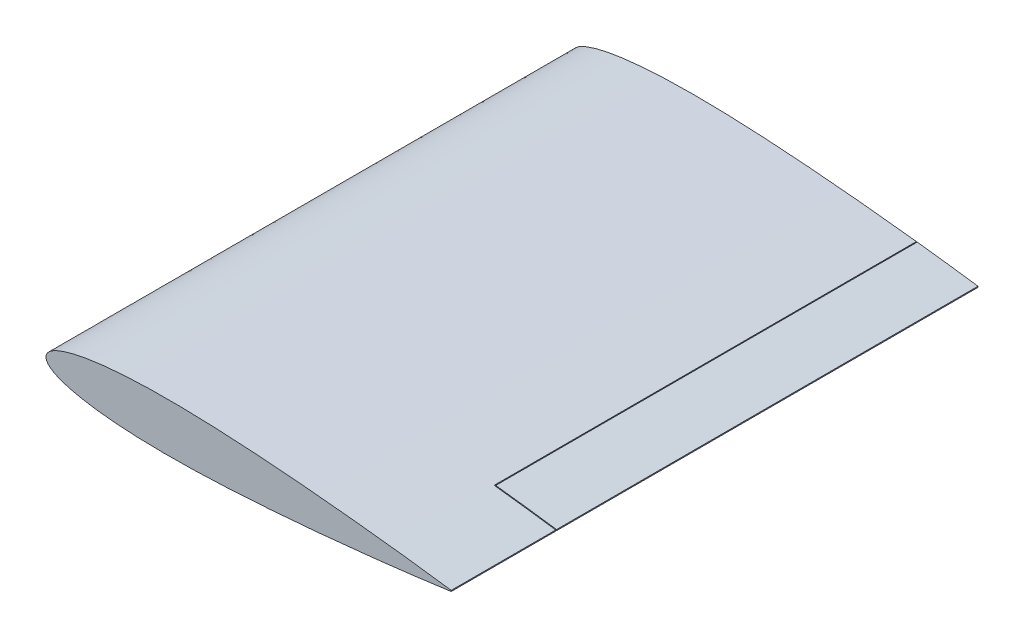
SolidWorks part; units mm, degrees
ref_plane "Front Plane" through (0, 0, 0) normal (0, 0, 1) x (1, 0, 0)
ref_plane "Top Plane" through (0, 0, 0) normal (0, 1, 0) x (1, 0, 0)
ref_plane "Right Plane" through (0, 0, 0) normal (1, 0, 0) x (0, 0, -1)
curve "Curve1"
  spline degree 3 poles (0, 0, 0) (0.003, 0.0365, 0) (0.009, 0.1114, 0) (0.0578, 0.22, 0) (0.134, 0.3245, 0) (0.2397, 0.4254, 0) (0.3736, 0.523, 0) (0.536, 0.6174, 0) (0.7264, 0.7086, 0) (0.9445, 0.7962, 0) (1.1898, 0.8801, 0) (1.462, 0.96, 0) (1.7603, 1.0355, 0) (2.0841, 1.1065, 0) (2.4327, 1.1725, 0) (2.8052, 1.2334, 0) (3.2008, 1.2888, 0) (3.6185, 1.3388, 0) (4.0575, 1.3829, 0) (4.5166, 1.4212, 0) (4.9948, 1.4535, 0) (5.491, 1.4798, 0) (6.0041, 1.5001, 0) (6.5327, 1.5144, 0) (7.0758, 1.5227, 0) (7.632, 1.5254, 0) (8.2001, 1.5224, 0) (8.7786, 1.514, 0) (9.3663, 1.5004, 0) (9.9618, 1.4819, 0) (10.5636, 1.4587, 0) (11.1705, 1.4311, 0) (11.7809, 1.3995, 0) (12.3935, 1.3642, 0) (13.0067, 1.3254, 0) (13.6193, 1.2836, 0) (14.2297, 1.2391, 0) (14.8366, 1.1921, 0) (15.4384, 1.1431, 0) (16.0339, 1.0922, 0) (16.6216, 1.0399, 0) (17.2001, 0.9864, 0) (17.7681, 0.9321, 0) (18.3242, 0.8771, 0) (18.8673, 0.8219, 0) (19.3959, 0.7666, 0) (19.9089, 0.7116, 0) (20.405, 0.657, 0) (20.8832, 0.6033, 0) (21.3422, 0.5505, 0) (21.7811, 0.499, 0) (22.1987, 0.449, 0) (22.5942, 0.4008, 0) (22.9666, 0.3545, 0) (23.3149, 0.3106, 0) (23.6385, 0.2691, 0) (23.9366, 0.2304, 0) (24.2084, 0.1946, 0) (24.4533, 0.1619, 0) (24.6708, 0.1326, 0) (24.8603, 0.1068, 0) (25.0214, 0.0847, 0) (25.1537, 0.0664, 0) (25.257, 0.052, 0) (25.3309, 0.0417, 0) (25.3753, 0.0355, 0) (25.3951, 0.0327, 0) (25.4, 0.032, 0) knots 0 0 0 0 0.004218 0.008652 0.013562 0.019137 0.0255 0.032726 0.040862 0.04993 0.05994 0.070892 0.082777 0.095581 0.109286 0.123868 0.139301 0.155557 0.172602 0.190404 0.208924 0.228125 0.247965 0.268401 0.289388 0.310881 0.332832 0.35519 0.377906 0.400928 0.424203 0.447679 0.471299 0.49501 0.518757 0.542484 0.566136 0.589657 0.612992 0.636087 0.658886 0.681338 0.703388 0.724985 0.746079 0.766619 0.786556 0.805845 0.82444 0.842296 0.859372 0.875627 0.891023 0.905523 0.919093 0.9317 0.943314 0.953909 0.963457 0.971937 0.979328 0.985613 0.990775 0.994804 0.997688 0.999422 1 1 1 1
curve "Curve2"
  spline degree 3 poles (0.0148, -0.1082, 0) (0.028, -0.1443, 0) (0.0559, -0.2205, 0) (0.1346, -0.3244, 0) (0.2395, -0.4254, 0) (0.3737, -0.523, 0) (0.536, -0.6174, 0) (0.7264, -0.7086, 0) (0.9445, -0.7962, 0) (1.1898, -0.8801, 0) (1.462, -0.96, 0) (1.7603, -1.0355, 0) (2.0841, -1.1065, 0) (2.4327, -1.1725, 0) (2.8052, -1.2334, 0) (3.2008, -1.2888, 0) (3.6185, -1.3388, 0) (4.0575, -1.3829, 0) (4.5166, -1.4212, 0) (4.9948, -1.4535, 0) (5.491, -1.4798, 0) (6.0041, -1.5001, 0) (6.5327, -1.5144, 0) (7.0758, -1.5227, 0) (7.632, -1.5254, 0) (8.2001, -1.5224, 0) (8.7786, -1.514, 0) (9.3663, -1.5004, 0) (9.9618, -1.4819, 0) (10.5636, -1.4587, 0) (11.1705, -1.4311, 0) (11.7809, -1.3995, 0) (12.3935, -1.3642, 0) (13.0067, -1.3254, 0) (13.6193, -1.2836, 0) (14.2297, -1.2391, 0) (14.8366, -1.1921, 0) (15.4384, -1.1431, 0) (16.0339, -1.0922, 0) (16.6216, -1.0399, 0) (17.2001, -0.9864, 0) (17.7681, -0.9321, 0) (18.3242, -0.8771, 0) (18.8673, -0.8219, 0) (19.3959, -0.7666, 0) (19.9089, -0.7116, 0) (20.405, -0.657, 0) (20.8832, -0.6033, 0) (21.3422, -0.5505, 0) (21.7811, -0.499, 0) (22.1987, -0.449, 0) (22.5942, -0.4008, 0) (22.9666, -0.3545, 0) (23.3149, -0.3106, 0) (23.6385, -0.2691, 0) (23.9366, -0.2304, 0) (24.2084, -0.1946, 0) (24.4533, -0.1619, 0) (24.6708, -0.1326, 0) (24.8603, -0.1068, 0) (25.0214, -0.0847, 0) (25.1537, -0.0664, 0) (25.257, -0.052, 0) (25.3309, -0.0417, 0) (25.3753, -0.0355, 0) (25.3951, -0.0327, 0) (25.4, -0.032, 0) knots 0 0 0 0 0.004453 0.009384 0.014983 0.021372 0.028629 0.036799 0.045906 0.055959 0.066957 0.078892 0.091751 0.105513 0.120157 0.135656 0.15198 0.169098 0.186975 0.205574 0.224856 0.24478 0.265302 0.286379 0.307962 0.330006 0.352459 0.375271 0.398391 0.421765 0.445339 0.46906 0.492871 0.516719 0.540546 0.564298 0.587919 0.611353 0.634545 0.657442 0.679988 0.702132 0.723821 0.745003 0.76563 0.785652 0.805023 0.823696 0.841628 0.858776 0.8751 0.890561 0.905123 0.91875 0.93141 0.943074 0.953713 0.963302 0.971818 0.979241 0.985552 0.990736 0.994782 0.997678 0.999419 1 1 1 1
sketch "Sketch1" plane through (0, 0, 0) normal (0, 0, 1) x (1, 0, 0)
  line L0 (0, 0) -> (0.0742, -0.5411)
  line L1 (127, 0.16) -> (127, -0.16)
  spline S2 degree 3 poles (0.0742, -0.5411) (0.1402, -0.7217) (0.2794, -1.1023) (0.673, -1.6219) (1.1974, -2.1272) (1.8685, -2.615) (2.6798, -3.0872) (3.6318, -3.5429) (4.7223, -3.9812) (5.9492, -4.4007) (7.31, -4.8) (8.8016, -5.1777) (10.4206, -5.5323) (12.1634, -5.8624) (14.0259, -6.1668) (16.0039, -6.4442) (18.0926, -6.6938) (20.2874, -6.9146) (22.583, -7.106) (24.9741, -7.2675) (27.4552, -7.3989) (30.0204, -7.5003) (32.6637, -7.5718) (35.3791, -7.6137) (38.1601, -7.6269) (41.0003, -7.6119) (43.8929, -7.5699) (46.8314, -7.5019) (49.8088, -7.4093) (52.8181, -7.2933) (55.8524, -7.1556) (58.9045, -6.9976) (62.9897, -6.7619) (67.0743, -6.4928) (72.1532, -6.1221) (77.1616, -5.7236) (82.1152, -5.2913) (86.9285, -4.8463) (91.5567, -4.3963) (96.0742, -3.9303) (100.3424, -3.4723) (104.3213, -3.0299) (108.8003, -2.5098) (112.8562, -2.0199) (115.9539, -1.6325) (118.1927, -1.3456) (120.4545, -1.0515) (122.9821, -0.715) (125.1839, -0.4131) (126.3836, -0.2463) (126.7779, -0.1912) (127, -0.16) knots 0 0 0 0 0.004453 0.009384 0.014983 0.021372 0.028629 0.036799 0.045906 0.055959 0.066957 0.078892 0.091751 0.105513 0.120157 0.135656 0.15198 0.169098 0.186975 0.205574 0.224856 0.24478 0.265302 0.286379 0.307962 0.330006 0.352459 0.375271 0.398391 0.421765 0.445339 0.46906 0.492871 0.540546 0.564298 0.611353 0.657442 0.679988 0.723821 0.76563 0.785652 0.823696 0.858776 0.890561 0.91875 0.93141 0.943074 0.971818 0.990736 0.994782 1 1 1 1
  spline S3 degree 3 poles (0, 0) (0.0148, 0.1826) (0.0451, 0.5571) (0.2892, 1.1001) (0.6698, 1.6226) (1.1984, 2.127) (1.8682, 2.615) (2.6799, 3.0872) (3.6318, 3.5429) (4.7223, 3.9812) (5.9492, 4.4007) (7.31, 4.8) (8.8016, 5.1777) (10.4206, 5.5323) (12.1634, 5.8624) (14.0259, 6.1668) (16.0039, 6.4442) (18.0926, 6.6938) (20.2874, 6.9146) (22.583, 7.106) (24.9741, 7.2675) (27.4552, 7.3989) (30.0204, 7.5003) (32.6637, 7.5718) (35.3791, 7.6137) (38.1601, 7.6269) (41.0003, 7.6119) (43.8929, 7.5699) (46.8314, 7.5019) (49.8088, 7.4093) (52.8181, 7.2933) (55.8524, 7.1556) (58.9045, 6.9976) (62.9897, 6.7619) (67.0743, 6.4928) (72.1532, 6.1221) (77.1616, 5.7236) (82.1152, 5.2913) (86.9285, 4.8463) (91.5567, 4.3963) (96.0742, 3.9303) (100.3424, 3.4723) (104.3213, 3.0299) (108.8003, 2.5098) (112.8562, 2.0199) (115.9539, 1.6325) (118.1927, 1.3456) (120.4545, 1.0515) (122.9821, 0.715) (125.1839, 0.4131) (126.3836, 0.2463) (126.7779, 0.1912) (127, 0.16) knots 0 0 0 0 0.004218 0.008652 0.013562 0.019137 0.0255 0.032726 0.040862 0.04993 0.05994 0.070892 0.082777 0.095581 0.109286 0.123868 0.139301 0.155557 0.172602 0.190404 0.208924 0.228125 0.247965 0.268401 0.289388 0.310881 0.332832 0.35519 0.377906 0.400928 0.424203 0.447679 0.471299 0.49501 0.542484 0.566136 0.612992 0.658886 0.681338 0.724985 0.766619 0.786556 0.82444 0.859372 0.891023 0.919093 0.9317 0.943314 0.971937 0.990775 0.994804 1 1 1 1
  point P0 (127, 0)
  dimension "D1" = 127
extrude "Boss-Extrude1" add sketch "Sketch1" along normal blind 165.1
sketch "Sketch2" plane through (0, 0, 0) normal (0, 1, 0) x (1, 0, 0)
  line L0 (127, -165.1) -> (127, 0) construction
  line L1 (107.95, 0) -> (127, 0)
  line L2 (107.95, 0) -> (107.95, -132.08)
  line L3 (107.95, -132.08) -> (127, -132.08)
  line L4 (127, 0) -> (127, -132.08)
  dimension "D1" = 132.08
  dimension "D2" = 19.05
extrude "Cut-Extrude-Thin1" cut sketch "Sketch2" against normal blind 25.4 and the other way blind 25.4 thin thin type one direction wall 0.254
equation "\"span\"= 48"
equation "\"wing_chord\"= 9"
equation "\"fuse_len\"= 15"
equation "\"fuse_height\"= 5"
equation "\"fuse_wid\"= 5"
equation "\"foam_t\"= 0.1875"
equation "\"main_spar_len\"= 36"
equation "\"x_fuse_to_wing\"= 3"
equation "\"x_cg_from_le\"= 2.25"
equation "\"boom_len\"= 30"
equation "\"wing_angle\"= 1.5"
equation "\"boom_d\"= 0.75"
equation "\"wing_spar_d\"= 0.375"
equation "\"wing_spar_l\"= 48"
equation "\"wing_spar_spacing\"= 1.35"
equation "\"wing_mount_l\"= 2.5"
equation "\"vstab_span\"= 6.5"
equation "\"hstab_span\"= 15.25"
equation "\"tail_chord\"= 5"
equation "\"D1@Boss-Extrude1\"= \"vstab_span\""
equation "\"D1@Sketch2\"=\"vstab_span\"*0.8"
equation "\"D2@Sketch2\"=\"tail_chord\"*0.15"
